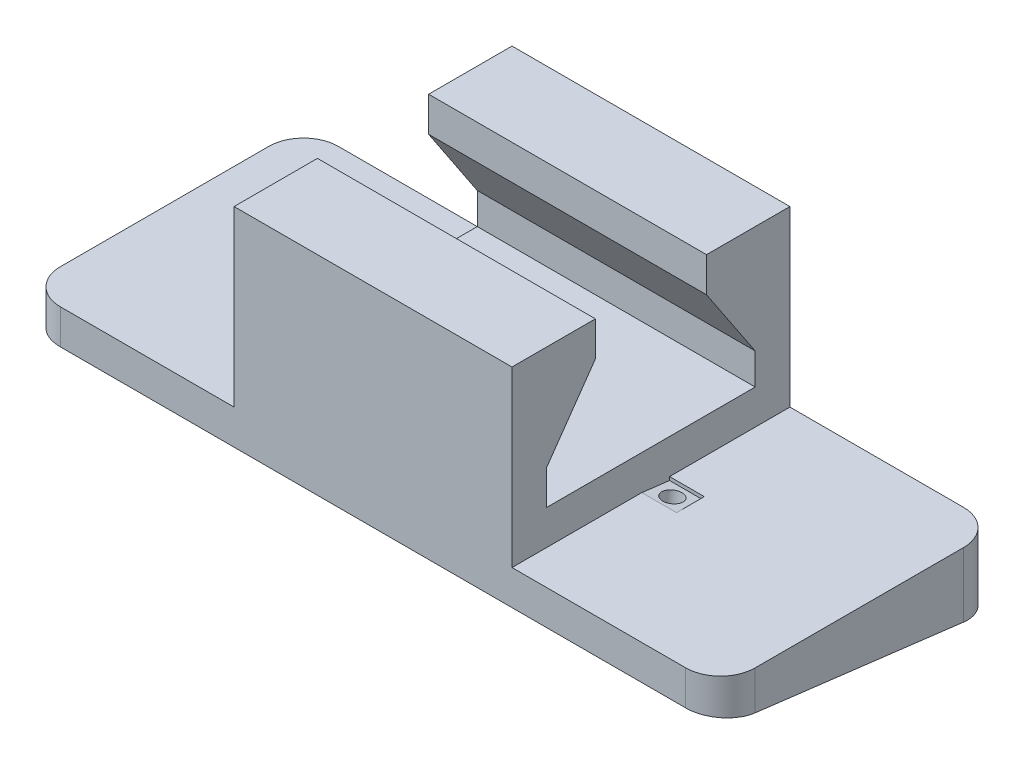
SolidWorks part; units mm, degrees
ref_plane "Front Plane" through (0, 0, 0) normal (0, 0, 1) x (1, 0, 0)
ref_plane "Top Plane" through (0, 0, 0) normal (0, 1, 0) x (1, 0, 0)
ref_plane "Right Plane" through (0, 0, 0) normal (1, 0, 0) x (0, 0, -1)
sketch "Sketch1" plane through (0, 0, 0) normal (0, 1, 0) x (1, 0, 0)
  line L0 (0, 0) -> (0, 20)
  line L1 (-50, 20) -> (50, 20)
  line L2 (-50, 20) -> (-50, -20)
  line L3 (-50, -20) -> (50, -20)
  line L4 (50, 20) -> (50, -20)
  dimension "D1" = 100
  dimension "D2" = 40
  dimension "D3" = 90
  dimension "D4" = 20
extrude "Boss-Extrude1" add sketch "Sketch1" along normal blind 5
sketch "Sketch3" plane through (0, 5, 0) normal (0, 1, 0) x (1, 0, 0)
  line L0 (0, 20) -> (-20, 20)
  line L1 (-50, 20) -> (50, 20) construction
  line L2 (-20, 20) -> (-20, -20)
  line L3 (-50, -20) -> (50, -20) construction
  line L4 (-20, -20) -> (20, -20)
  line L5 (20, -20) -> (20, 20)
  line L6 (20, 20) -> (0, 20)
  dimension "D1" = 40
  dimension "D2" = 20
extrude "Boss-Extrude2" add sketch "Sketch3" along normal blind 5
sketch "Sketch4" plane through (0, 10, 0) normal (0, 1, 0) x (1, 0, 0)
  line L0 (20, -20) -> (20, 20) construction
  line L1 (-20, 20) -> (20, 20)
  line L2 (-20, 20) -> (-20, 8)
  line L3 (-20, 8) -> (20, 8)
  line L4 (20, 20) -> (20, 8)
  line L5 (-20, 20) -> (-20, -20) construction
  line L6 (-20, -8) -> (20, -8)
  line L7 (-20, -8) -> (-20, -20)
  line L8 (-20, -20) -> (20, -20)
  line L9 (20, -8) -> (20, -20)
  line L10 (20, -20) -> (20, 20) construction
  line L11 (-20, -20) -> (20, -20) construction
  dimension "D1" = 12
  dimension "D2" = 12
extrude "Boss-Extrude3" add sketch "Sketch4" along normal blind 20
sketch "Sketch10" plane through (20, 0, 0) normal (1, 0, 0) x (0, 0, -1)
  line L0 (-8, 10) -> (-15, 10)
  line L2 (-8, 30) -> (-8, 10) construction
  line L3 (-8, 25) -> (-8, 10)
  line L4 (8, 10) -> (15, 10)
  line L6 (8, 30) -> (8, 10) construction
  line L7 (8, 25) -> (8, 10)
  line L8 (-15, 10) -> (-15, 15)
  line L9 (-15, 15) -> (-8, 25)
  line L10 (15, 10) -> (15, 14.5)
  line L11 (15, 14.5) -> (8, 25)
  dimension "D1" = 7
  dimension "D2" = 5
  dimension "D3" = 7
  dimension "D4" = 5
  dimension "D5" = 4.5
  dimension "D6" = 12.2066
extrude "Cut-Extrude2" cut sketch "Sketch10" against normal blind 70
sketch "Sketch11" plane through (-50, 0, 0) normal (-1, 0, 0) x (0, 0, 1)
  line L0 (20, 0) -> (-20, -4.9114)
  line L1 (-20, -4.9114) -> (-20, 0)
  line L2 (-20, 0) -> (20, 0)
  line L4 (-20, 0) -> (20, 0) construction
  dimension "D1" = 7
extrude "Boss-Extrude5" add sketch "Sketch11" against normal blind 100
sketch "Sketch12" plane through (0, -2.4192, 0.297) normal (0, -0.9925, 0.1219) x (1, 0, 0)
  circle A0 centre (-22.5, 0) radius 1.4
  circle A1 centre (22.5, 0) radius 1.4
  dimension "D1" = 45
  dimension "D2" = 22.5
extrude "Cut-Extrude3" cut sketch "Sketch12" against normal blind 10
sketch "Sketch16" plane through (-50, 0, 0) normal (-1, 0, 0) x (0, 0, 1)
  line L0 (-2.6536, 5) -> (1.3464, 5)
  line L1 (-20, 5) -> (20, 5) construction
  line L2 (-2.6536, 5) -> (-2.6536, 4.5089)
  line L3 (-2.6536, 4.5089) -> (1.3464, 5)
  point P4 (0, 0)
  point P6 (0, 0)
  dimension "D1" = 7
  dimension "D2" = 4
extrude "Cut-Extrude4" cut sketch "Sketch16" against normal blind 30
sketch "Sketch17" plane through (-50, 0, 0) normal (-1, 0, 0) x (0, 0, 1)
  line L0 (-2.6536, 5) -> (-2.6536, 4.5089)
  line L1 (-2.6536, 4.5089) -> (1.3464, 5)
  line L2 (1.3464, 5) -> (-2.6536, 5)
extrude "Boss-Extrude6" add sketch "Sketch17" against normal blind 25
sketch "Sketch18" plane through (50, 0, 0) normal (1, 0, 0) x (0, 0, -1)
  line L0 (2.6794, 5) -> (-1.3206, 5)
  line L1 (20, 5) -> (-20, 5) construction
  line L2 (-1.3206, 5) -> (2.6794, 4.5089)
  line L3 (2.6794, 4.5089) -> (2.6794, 5)
  dimension "D1" = 7
  dimension "D2" = 4
extrude "Cut-Extrude5" cut sketch "Sketch18" against normal blind 30
sketch "Sketch19" plane through (50, 0, 0) normal (1, 0, 0) x (0, 0, -1)
  line L0 (2.6794, 4.5089) -> (2.6794, 5)
  line L1 (2.6794, 5) -> (-1.3206, 5)
  line L2 (-1.3206, 5) -> (2.6794, 4.5089)
extrude "Boss-Extrude7" add sketch "Sketch19" against normal blind 25
fillet "Fillet1" radius 5 4 edges at (-50, 2.5, 20) (50, 2.5, 20) (50, 0.0443, -20) (-50, 0.0443, -20)
